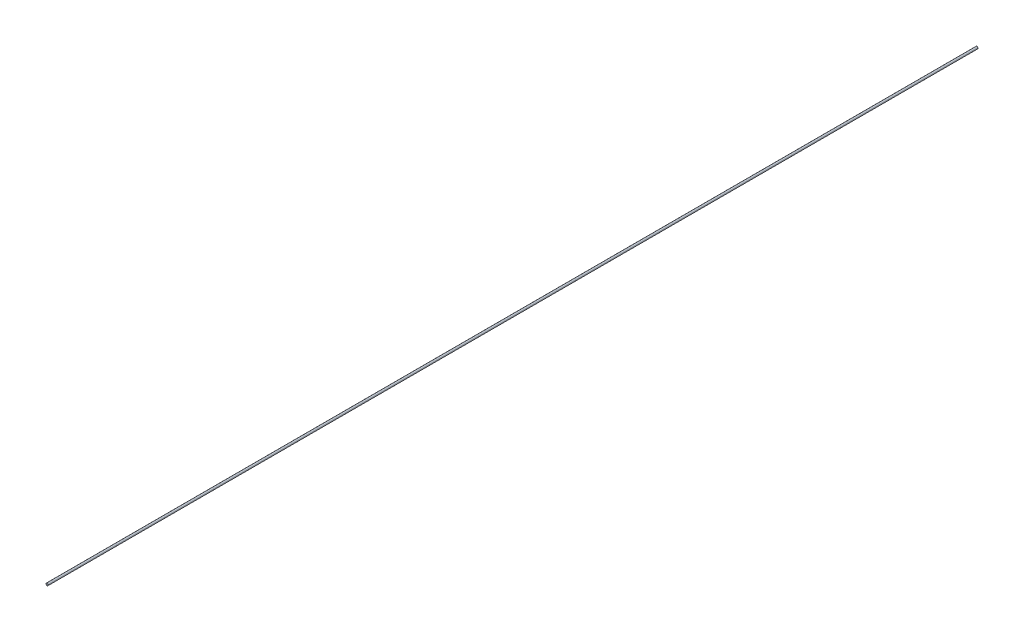
SolidWorks part; units mm, degrees
ref_plane "Front Plane" through (0, 0, 0) normal (0, 0, 1) x (1, 0, 0)
ref_plane "Top Plane" through (0, 0, 0) normal (0, 1, 0) x (1, 0, 0)
ref_plane "Right Plane" through (0, 0, 0) normal (1, 0, 0) x (0, 0, -1)
sketch "Sketch1" plane through (0, 0, 0) normal (0, 0, 1) x (1, 0, 0)
  circle A0 centre (0, 0) radius 0.3556
  dimension "D1" = 0.7112
extrude "Boss-Extrude1" add sketch "Sketch1" along normal blind 304.8
